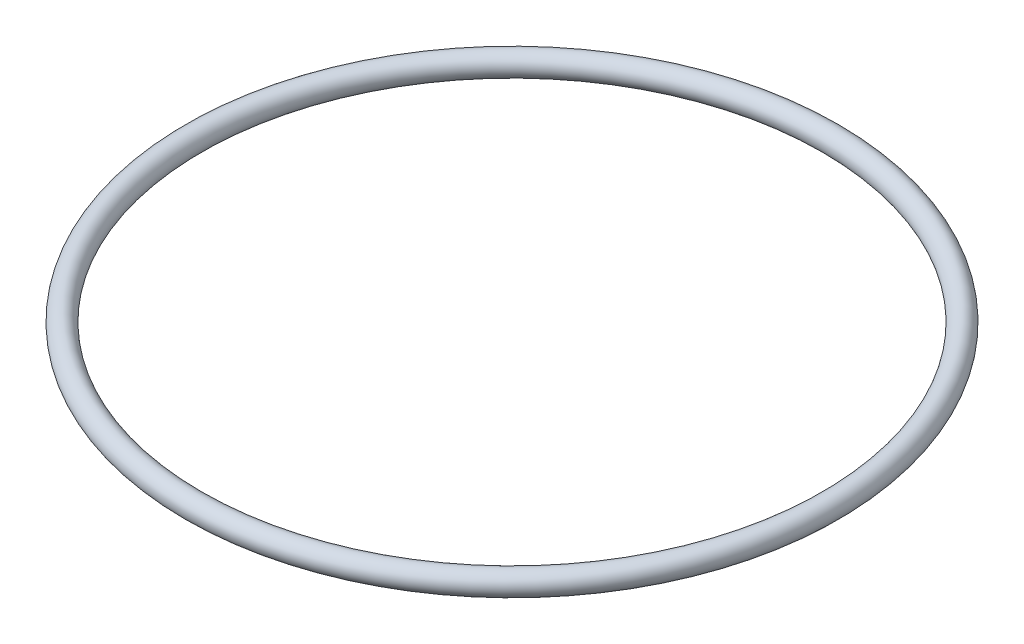
SolidWorks part; units mm, degrees
ref_plane "Front Plane" through (0, 0, 0) normal (0, 0, 1) x (1, 0, 0)
ref_plane "Top Plane" through (0, 0, 0) normal (0, 1, 0) x (1, 0, 0)
ref_plane "Right Plane" through (0, 0, 0) normal (1, 0, 0) x (0, 0, -1)
sketch "Sketch1" plane through (0, 0, 0) normal (0, 1, 0) x (1, 0, 0)
  circle A0 centre (0, 0) radius 33.8
  dimension "D1" = 67.6
sweep "Sweep1" add path "Sketch1" circular profile diameter 2.4 parameters "D3"=2.4
